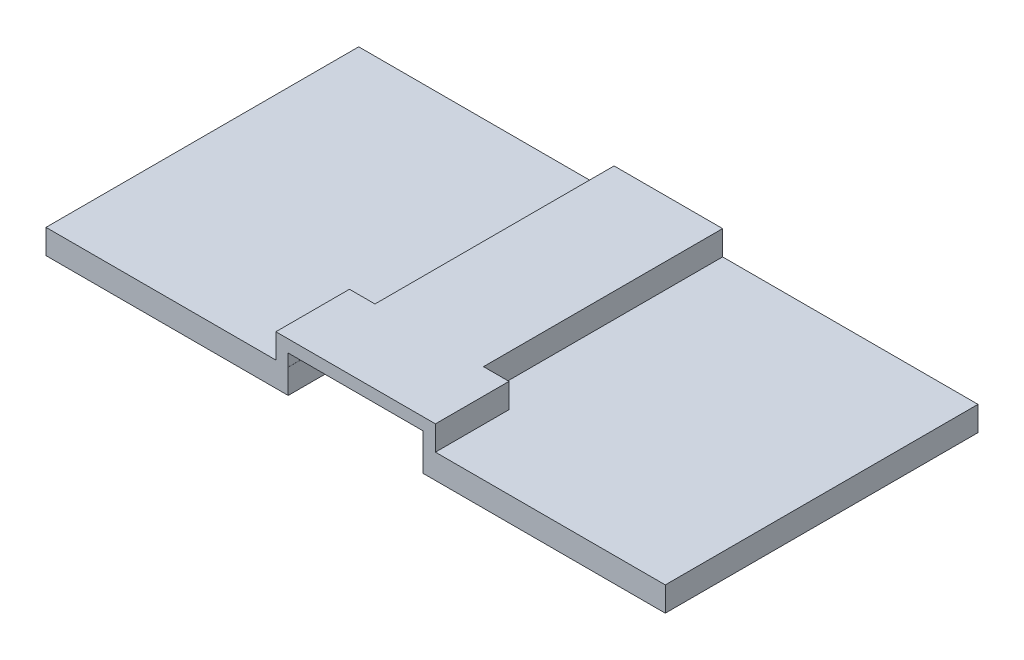
SolidWorks part; units mm, degrees
ref_plane "Front Plane" through (0, 0, 0) normal (0, 0, 1) x (1, 0, 0)
ref_plane "Top Plane" through (0, 0, 0) normal (0, 1, 0) x (1, 0, 0)
ref_plane "Right Plane" through (0, 0, 0) normal (1, 0, 0) x (0, 0, -1)
sketch "Sketch1" plane through (0, 0, 0) normal (0, 1, 0) x (1, 0, 0)
  line L1 (-18.5829, 8.6176) -> (31.9171, 8.6176)
  line L2 (-18.5829, 8.6176) -> (-18.5829, -16.8824)
  line L3 (-18.5829, -16.8824) -> (31.9171, -16.8824)
  line L4 (31.9171, 8.6176) -> (31.9171, -16.8824)
  dimension "D1" = 50.5
  dimension "D2" = 25.5
extrude "Boss-Extrude1" add sketch "Sketch1" along normal blind 2
sketch "Sketch2" plane through (0, 2, 0) normal (0, 1, 0) x (1, 0, 0)
  line L0 (-18.5829, 8.6176) -> (-18.5829, -16.8824) construction
  line L1 (1.1671, -11.8824) -> (12.1671, -11.8824)
  line L2 (1.1671, -11.8824) -> (1.1671, -16.8824)
  line L3 (1.1671, -16.8824) -> (12.1671, -16.8824)
  line L4 (12.1671, -11.8824) -> (12.1671, -16.8824)
  line L5 (-18.5829, -16.8824) -> (31.9171, -16.8824) construction
  point P4 (0, 0)
  dimension "D1" = 11
  dimension "D2" = 5
  dimension "D3" = 19.75
  dimension "D4" = 0
extrude "Cut-Extrude1" cut sketch "Sketch2" against normal blind 2
sketch "Sketch3" plane through (0, 2, 0) normal (0, 1, 0) x (1, 0, 0)
  line L0 (31.9171, 8.6176) -> (-18.5829, 8.6176) construction
  line L1 (2.2421, 8.6176) -> (11.0921, 8.6176)
  line L2 (2.2421, 8.6176) -> (2.2421, -11.8824)
  line L3 (2.2421, -11.8824) -> (11.0921, -11.8824)
  line L4 (11.0921, 8.6176) -> (11.0921, -11.8824)
  line L5 (12.1671, -11.8824) -> (1.1671, -11.8824) construction
  line L6 (12.1671, -16.8824) -> (12.1671, -11.8824) construction
  dimension "D1" = 8.85
  dimension "D2" = 0
  dimension "D3" = 0
  dimension "D4" = 1.075
extrude "Boss-Extrude2" add sketch "Sketch3" along normal blind 1 separate body
other "Move Face1" face at (6.6671, 3, 1.6324) parameters "D1"=1
sketch "Sketch4" plane through (0, 0, 11.8824) normal (0, 0, 1) x (1, 0, 0)
  line L0 (11.0921, 4) -> (11.0921, 2) construction
  line L1 (2.2421, 4) -> (11.0921, 4)
  line L2 (2.2421, 4) -> (2.2421, 3)
  line L3 (2.2421, 3) -> (11.0921, 3)
  line L4 (11.0921, 4) -> (11.0921, 3)
extrude "Boss-Extrude3" add sketch "Sketch4" along normal blind 5
sketch "Sketch5" plane through (2.2421, 0, 0) normal (-1, 0, 0) x (0, 0, 1)
  line L0 (-8.6176, 4) -> (16.8824, 4) construction
  line L1 (16.8824, 3) -> (11.8824, 3)
  line L2 (16.8824, 3) -> (16.8824, 4)
  line L3 (16.8824, 4) -> (11.8824, 4)
  line L4 (11.8824, 3) -> (11.8824, 4)
  dimension "D1" = 5
extrude "Boss-Extrude4" add sketch "Sketch5" along normal blind 2 and the other way blind 11
other "Move Face3" face at (13.2421, 3.5, 14.3824) parameters "D1"=0.15
other "Move Face4" face at (0.2421, 3.5, 14.3824) parameters "D1"=0.08
other "Move Face5" face at (13.0921, 3.5, 14.3824) parameters "D1"=0.08
sketch "Sketch8" plane through (0, 3, 0) normal (0, -1, 0) x (1, 0, 0)
  line L0 (0.1621, 16.8824) -> (13.1721, 16.8824) construction
  line L1 (0.1621, 11.8824) -> (1.1621, 11.8824)
  line L2 (0.1621, 11.8824) -> (0.1621, 16.8824)
  line L3 (0.1621, 16.8824) -> (1.1621, 16.8824)
  line L4 (1.1621, 11.8824) -> (1.1621, 16.8824)
  line L6 (13.1721, 11.8824) -> (12.1721, 11.8824)
  line L7 (13.1721, 11.8824) -> (13.1721, 16.8824)
  line L8 (13.1721, 16.8824) -> (12.1721, 16.8824)
  line L9 (12.1721, 11.8824) -> (12.1721, 16.8824)
  dimension "D1" = 1
  dimension "D2" = 1
extrude "Boss-Extrude5" add sketch "Sketch8" along normal blind 1
sketch "Sketch9" plane through (0, 2, 0) normal (0, 1, 0) x (1, 0, 0)
  line L0 (13.1721, -11.8824) -> (13.1721, -16.8824) construction
  line L1 (11.0921, -11.8824) -> (13.1721, -11.8824)
  line L2 (11.0921, -11.8824) -> (11.0921, -10.8824)
  line L3 (11.0921, -10.8824) -> (13.1721, -10.8824)
  line L4 (13.1721, -11.8824) -> (13.1721, -10.8824)
  dimension "D1" = 0
  dimension "D2" = 1
extrude "Boss-Extrude6" add sketch "Sketch9" along normal blind 2
sketch "Sketch10" plane through (0, 2, 0) normal (0, 1, 0) x (1, 0, 0)
  line L0 (0.1621, -16.8824) -> (0.1621, -11.8824) construction
  line L1 (2.2421, -11.8824) -> (0.1621, -11.8824)
  line L2 (2.2421, -11.8824) -> (2.2421, -10.8824)
  line L3 (2.2421, -10.8824) -> (0.1621, -10.8824)
  line L4 (0.1621, -11.8824) -> (0.1621, -10.8824)
  dimension "D1" = 0
  dimension "D2" = 1
extrude "Boss-Extrude7" add sketch "Sketch10" along normal blind 2
